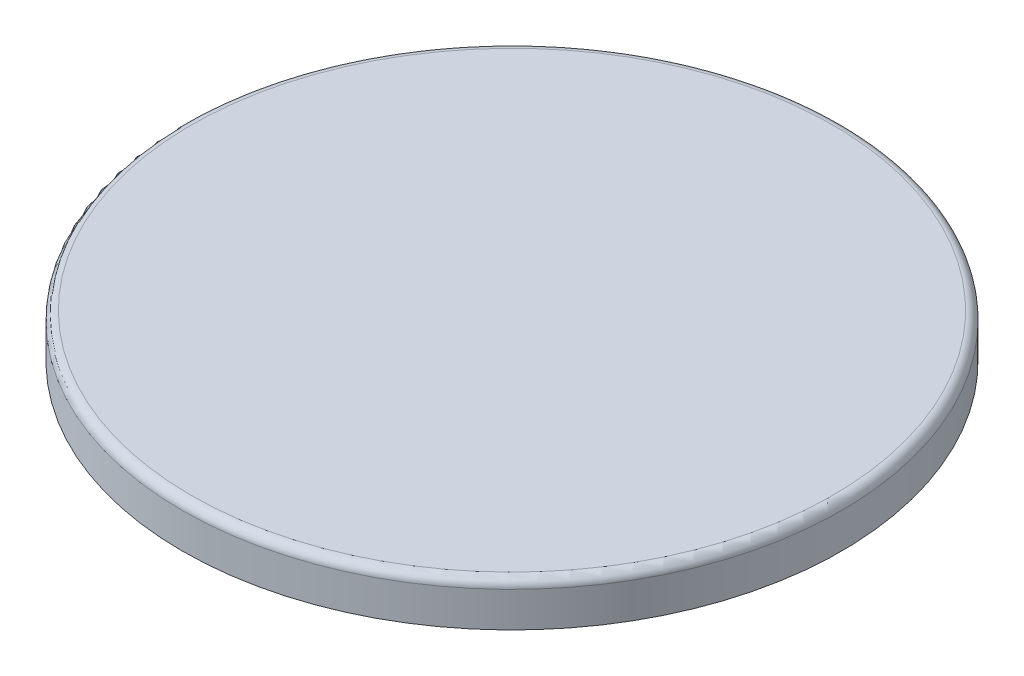
SolidWorks part; units mm, degrees
ref_plane "前视基准面" through (0, 0, 0) normal (0, 0, 1) x (1, 0, 0)
ref_plane "上视基准面" through (0, 0, 0) normal (0, 1, 0) x (1, 0, 0)
ref_plane "右视基准面" through (0, 0, 0) normal (1, 0, 0) x (0, 0, -1)
other "Configuration Table"
sketch "草图1" plane through (0, 0, 0) normal (0, 1, 0) x (1, 0, 0)
  circle A0 centre (0, 0) radius 15
  dimension "D1" = 30
extrude "凸台-拉伸1" add sketch "草图1" along normal blind 2
fillet "圆角1" radius 0.4 1 edges at (0, 2, 15)
